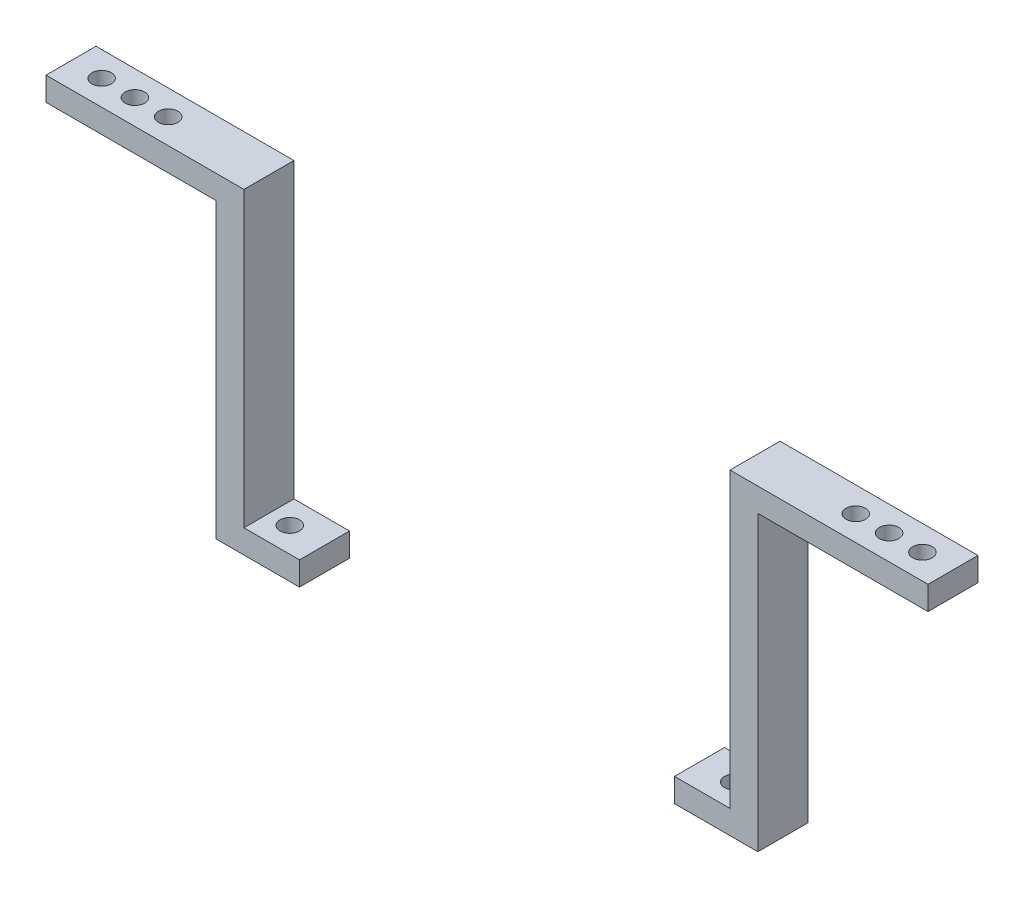
SolidWorks part; units mm, degrees
ref_plane "Front Plane" through (0, 0, 0) normal (0, 0, 1) x (1, 0, 0)
ref_plane "Top Plane" through (0, 0, 0) normal (0, 1, 0) x (1, 0, 0)
ref_plane "Right Plane" through (0, 0, 0) normal (1, 0, 0) x (0, 0, -1)
sketch "Sketch1" plane through (0, 0, 0) normal (0, 1, 0) x (1, 0, 0)
  line L0 (-34.29, 0) -> (0, 0) construction
  line L1 (-49.53, 4.572) -> (-34.29, 4.572)
  line L2 (-49.53, 4.572) -> (-49.53, -4.572)
  line L3 (-49.53, -4.572) -> (-34.29, -4.572)
  line L4 (-34.29, 4.572) -> (-34.29, -4.572)
  line L5 (34.29, 4.572) -> (49.53, 4.572)
  line L6 (34.29, 4.572) -> (34.29, -4.572)
  line L7 (34.29, -4.572) -> (49.53, -4.572)
  line L8 (49.53, 4.572) -> (49.53, -4.572)
  line L9 (0, 0) -> (34.29, 0) construction
  line L10 (-40.64, 0) -> (0, 0) construction
  line L11 (0, 0) -> (40.64, 0) construction
  line L12 (-40.64, -4.572) -> (-40.64, 0) construction
  line L14 (-40.64, 0) -> (-40.64, 4.572) construction
  circle A0 centre (-40.64, 0) radius 1.778
  circle A1 centre (40.64, 0) radius 1.778
  dimension "D2" = 3.556
  dimension "D1" = 34.29
  dimension "D3" = 40.64
  dimension "D4" = 9.144
  dimension "D5" = 8.89
  dimension "D6" = 49.53
extrude "Boss-Extrude1" add sketch "Sketch1" along normal blind 4.318
sketch "Sketch2" plane through (0, 4.318, 0) normal (0, 1, 0) x (1, 0, 0)
  line L0 (-49.53, -4.572) -> (-34.29, -4.572) construction
  line L1 (-49.53, 4.572) -> (-44.45, 4.572)
  line L2 (-49.53, 4.572) -> (-49.53, -4.572)
  line L3 (-49.53, -4.572) -> (-44.45, -4.572)
  line L4 (-44.45, 4.572) -> (-44.45, -4.572)
  line L5 (49.53, 4.572) -> (34.29, 4.572) construction
  line L6 (49.53, -4.572) -> (44.45, -4.572)
  line L7 (49.53, -4.572) -> (49.53, 4.572)
  line L8 (49.53, 4.572) -> (44.45, 4.572)
  line L9 (44.45, -4.572) -> (44.45, 4.572)
  dimension "D1" = 5.08
extrude "Boss-Extrude2" add sketch "Sketch2" along normal blind 49.276
sketch "Sketch3" plane through (0, 53.594, 0) normal (0, 1, 0) x (1, 0, 0)
  line L1 (-44.45, -4.572) -> (-80.645, -4.572)
  line L2 (-44.45, -4.572) -> (-44.45, 4.572)
  line L3 (-44.45, 4.572) -> (-80.645, 4.572)
  line L4 (-80.645, -4.572) -> (-80.645, 4.572)
  line L5 (44.45, -4.572) -> (80.645, -4.572)
  line L6 (44.45, -4.572) -> (44.45, 4.572)
  line L7 (44.45, 4.572) -> (80.645, 4.572)
  line L8 (80.645, -4.572) -> (80.645, 4.572)
extrude "Boss-Extrude3" add sketch "Sketch3" along normal blind 4.318
sketch "Sketch4" plane through (0, 57.912, 0) normal (0, 1, 0) x (1, 0, 0)
  line L0 (-75.057, 0) -> (0, 0) construction
  line L1 (0, 0) -> (75.057, 0) construction
  circle A0 centre (-75.057, 0) radius 1.778
  circle A1 centre (75.057, 0) radius 1.778
  dimension "D1" = 3.556
  dimension "D2" = 150.114
extrude "Cut-Extrude1" cut sketch "Sketch4" against normal through all
sketch "Sketch5" plane through (0, 57.912, 0) normal (0, 1, 0) x (1, 0, 0)
  line L0 (-75.057, 0) -> (-68.961, 0) construction
  line L1 (-68.961, 0) -> (-62.865, 0) construction
  line L2 (62.865, 0) -> (68.961, 0) construction
  line L3 (68.961, 0) -> (75.057, 0) construction
  circle A0 centre (-68.961, 0) radius 1.778
  circle A1 centre (-62.865, 0) radius 1.778
  circle A2 centre (62.865, 0) radius 1.778
  circle A3 centre (68.961, 0) radius 1.778
  dimension "D1" = 3.556
  dimension "D2" = 6.096
extrude "Cut-Extrude2" cut sketch "Sketch5" against normal through all
